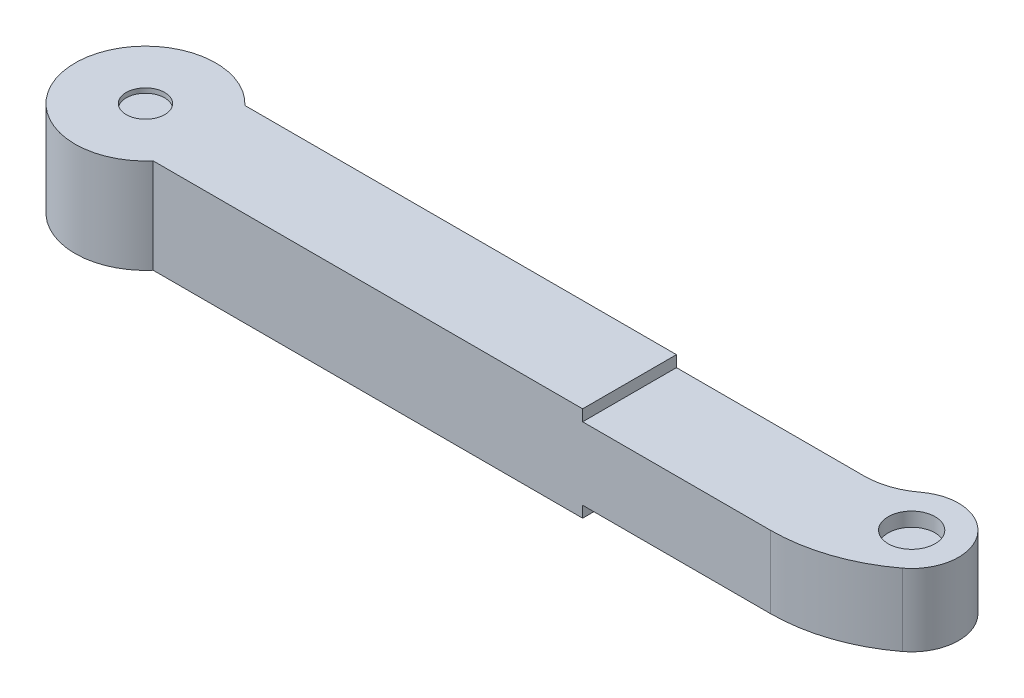
SolidWorks part; units mm, degrees
ref_plane "Alzado" through (0, 0, 0) normal (0, 0, 1) x (1, 0, 0)
ref_plane "Planta" through (0, 0, 0) normal (0, 1, 0) x (1, 0, 0)
ref_plane "Vista lateral" through (0, 0, 0) normal (1, 0, 0) x (0, 0, -1)
sketch "Croquis1" plane through (0, 0, 0) normal (0, 1, 0) x (1, 0, 0)
  line L1 (-32.8351, -4.9917) -> (32.9449, -4.9917)
  line L3 (-33.0551, 5.0083) -> (32.9449, 5.0083)
  line L4 (32.9449, -4.9917) -> (32.9449, 5.0083)
  line L5 (-32.8351, -4.9917) -> (32.9449, 5.0083) construction
  line L6 (-33.0551, 5.0083) -> (32.9449, -4.9917) construction
  arc A0 (-33.0551, 5.0083) -> (-32.8351, -4.9917) centre (-38.5328, -0.1146) ccw
  point P0 (0, 0)
  point P7 (-29.9944, -5.0009)
  point P8 (-33.0551, -4.9917)
  dimension "D3" = 15
  dimension "D1" = 10
  dimension "D2" = 66
extrude "Saliente-Extruir1" add sketch "Croquis1" along normal blind 10.1
sketch "Croquis7" plane through (0, 10.1, 0) normal (0, 1, 0) x (1, 0, 0)
  circle A0 centre (-38.5328, -0.1146) radius 2.05
  dimension "D1" = 4.1
extrude "Cortar-Extruir1" cut sketch "Croquis7" against normal blind 0.5
sketch "Croquis11" plane through (0, 0, 4.9917) normal (0, 0, 1) x (1, 0, 0)
  line L0 (-32.8351, 10.1) -> (32.9449, 10.1) construction
  line L1 (12.9449, 10.1) -> (32.9449, 10.1)
  line L2 (12.9449, 10.1) -> (12.9449, 8.9)
  line L3 (12.9449, 8.9) -> (32.9449, 8.9)
  line L4 (32.9449, 10.1) -> (32.9449, 8.9)
  line L5 (32.9449, 10.1) -> (32.9449, 0) construction
  line L6 (-32.8351, 0) -> (32.9449, 0) construction
  line L7 (12.9449, 0) -> (32.9449, 0)
  line L8 (12.9449, 0) -> (12.9449, 1.2)
  line L9 (12.9449, 1.2) -> (32.9449, 1.2)
  line L10 (32.9449, 0) -> (32.9449, 1.2)
  dimension "D1" = 20
  dimension "D2" = 1.2
  dimension "D3" = 0
  dimension "D4" = 0
extrude "Cortar-Extruir4" cut sketch "Croquis11" against normal through all
ref_plane "Plano1" through (0, 5.05, 0) normal (0, 1, 0) x (1, 0, 0)
sketch "Croquis13" plane through (0, 8.9, 0) normal (0, 1, 0) x (1, 0, 0)
sketch "Croquis14" plane through (0, 8.9, 0) normal (0, 1, 0) x (1, 0, 0)
  line L0 (32.9449, 5.0083) -> (32.9449, -4.9917) construction
  line L1 (12.9449, -4.9917) -> (32.9449, -4.9917) construction
  line L2 (32.9449, 5.0083) -> (32.9449, -4.9917)
  arc A0 (32.9449, 0.0083) -> (40.4851, 2.5386) centre (32.9449, 12.5083) ccw construction
  arc A1 (32.9449, -4.9917) -> (43.5012, -1.4493) centre (32.9449, 12.5083) ccw
  arc A2 (32.9449, 5.0083) -> (37.469, 6.5265) centre (32.9449, 12.5083) ccw
  arc A4 (43.5012, -1.4493) -> (37.469, 6.5265) centre (40.4851, 2.5386) ccw
  point P3 (36.7776, 0.6343)
  dimension "D1" = 5
  dimension "D2" = 17.5
extrude "Saliente-Extruir2" add sketch "Croquis14" against normal up to vertex
sketch "Croquis15" plane through (0, 8.9, 0) normal (0, 1, 0) x (1, 0, 0)
  circle A0 centre (40.4851, 2.5386) radius 2.5
  dimension "D1" = 5
extrude "Cortar-Extruir5" cut sketch "Croquis15" against normal blind 1.5
mirror "Simetría1" about plane through (0, 5.05, 0) normal (0, 1, 0) of "Cortar-Extruir5"
